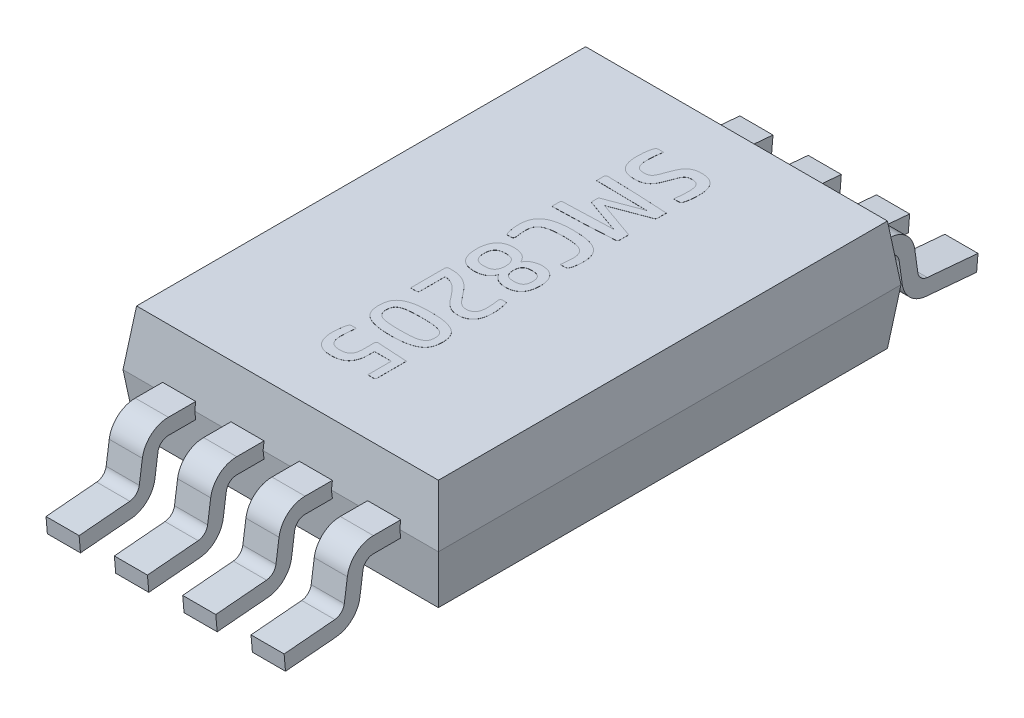
SolidWorks part; units mm, degrees
ref_plane "Front" through (0, 0, 0) normal (0, 0, 1) x (1, 0, 0)
ref_plane "Top" through (0, 0, 0) normal (0, 1, 0) x (1, 0, 0)
ref_plane "Right" through (0, 0, 0) normal (1, 0, 0) x (0, 0, -1)
sketch "Sketch1" plane through (0, 0, 0) normal (0, 1, 0) x (1, 0, 0)
  line L1 (-1.5, -2.2) -> (1.5, -2.2)
  line L2 (-1.5, -2.2) -> (-1.5, 2.2)
  line L3 (-1.5, 2.2) -> (1.5, 2.2)
  line L4 (1.5, -2.2) -> (1.5, 2.2)
  line L5 (-1.5, -2.2) -> (1.5, 2.2) construction
  line L6 (-1.5, 2.2) -> (1.5, -2.2) construction
  point P0 (0, 0)
  dimension "D1" = 3
  dimension "D2" = 4.4
extrude "Extrude1" add sketch "Sketch1" along normal mid plane 1.05 draft 7
ref_plane "Plane1" through (0.975, 0, 0) normal (1, 0, 0) x (0, 0, -1)
sketch "Sketch5" plane through (0.975, 0, 0) normal (1, 0, 0) x (0, 0, -1)
  line L0 (0, 0.075) -> (-2.451, 0.075)
  line L1 (-2.6985, -0.1402) -> (-2.7277, -0.3477)
  line L2 (-2.818, -0.4334) -> (-3.3, -0.4756)
  line L3 (-2.2, 0) -> (2.2, 0) construction
  line L4 (-2.1355, -0.525) -> (2.1355, -0.525) construction
  line L5 (-3.3, -0.4756) -> (-3.2869, -0.625)
  line L7 (0, -0.075) -> (-2.451, -0.075)
  line L8 (-2.55, -0.1611) -> (-2.5792, -0.3686)
  line L9 (-2.8049, -0.5828) -> (-3.2869, -0.625)
  line L10 (0, 0.075) -> (0, -0.075) construction
  line L11 (2.8049, -0.5828) -> (3.2869, -0.625)
  line L12 (2.55, -0.1611) -> (2.5792, -0.3686)
  line L13 (0, -0.075) -> (2.451, -0.075)
  line L14 (3.3, -0.4756) -> (3.2869, -0.625)
  line L15 (2.818, -0.4334) -> (3.3, -0.4756)
  line L16 (2.6985, -0.1402) -> (2.7277, -0.3477)
  line L17 (0, 0.075) -> (2.451, 0.075)
  arc A0 (-2.7277, -0.3477) -> (-2.818, -0.4334) centre (-2.8267, -0.3338) cw
  arc A1 (-2.451, 0.075) -> (-2.6985, -0.1402) centre (-2.451, -0.175) ccw
  arc A2 (-2.451, -0.075) -> (-2.55, -0.1611) centre (-2.451, -0.175) ccw
  arc A3 (-2.5792, -0.3686) -> (-2.8049, -0.5828) centre (-2.8267, -0.3338) cw
  arc A4 (2.5792, -0.3686) -> (2.8049, -0.5828) centre (2.8267, -0.3338) ccw
  arc A5 (2.451, -0.075) -> (2.55, -0.1611) centre (2.451, -0.175) cw
  arc A6 (2.451, 0.075) -> (2.6985, -0.1402) centre (2.451, -0.175) cw
  arc A7 (2.7277, -0.3477) -> (2.818, -0.4334) centre (2.8267, -0.3338) ccw
  arc A8 (-2.7277, -0.3477) -> (-2.818, -0.4334) centre (-2.8267, -0.3338) cw construction
  point P13 (-2.7388, -0.4265)
  dimension "D8" = 0.1
  dimension "D1" = 0.075
  dimension "D2" = 6.6
  dimension "D3" = 5
  dimension "D4" = 0.1
  dimension "D5" = 82
  dimension "D6" = 0.15
  dimension "D7" = 0.75
extrude "Extrude3" add sketch "Sketch5" along normal mid plane 0.315
pattern_linear "LPattern1" count 4 spacing 0.65 along (-1, 0, 0) of "Extrude3"
sketch "Sketch6" plane through (0, 0.525, 0) normal (0, 1, 0) x (1, 0, 0)
  line L0 (-0.2799, 2.1355) -> (-0.2799, -2.1355) construction
  line L1 (1.4355, 2.1355) -> (-1.4355, 2.1355) construction
  line L2 (-1.4355, -2.1355) -> (1.4355, -2.1355) construction
  text T0 "SMC8205" font "@Adobe Fan Heiti Std B" height 0.6
extrude "Boss-Extrude1" add sketch "Sketch6" along normal blind 0.001
